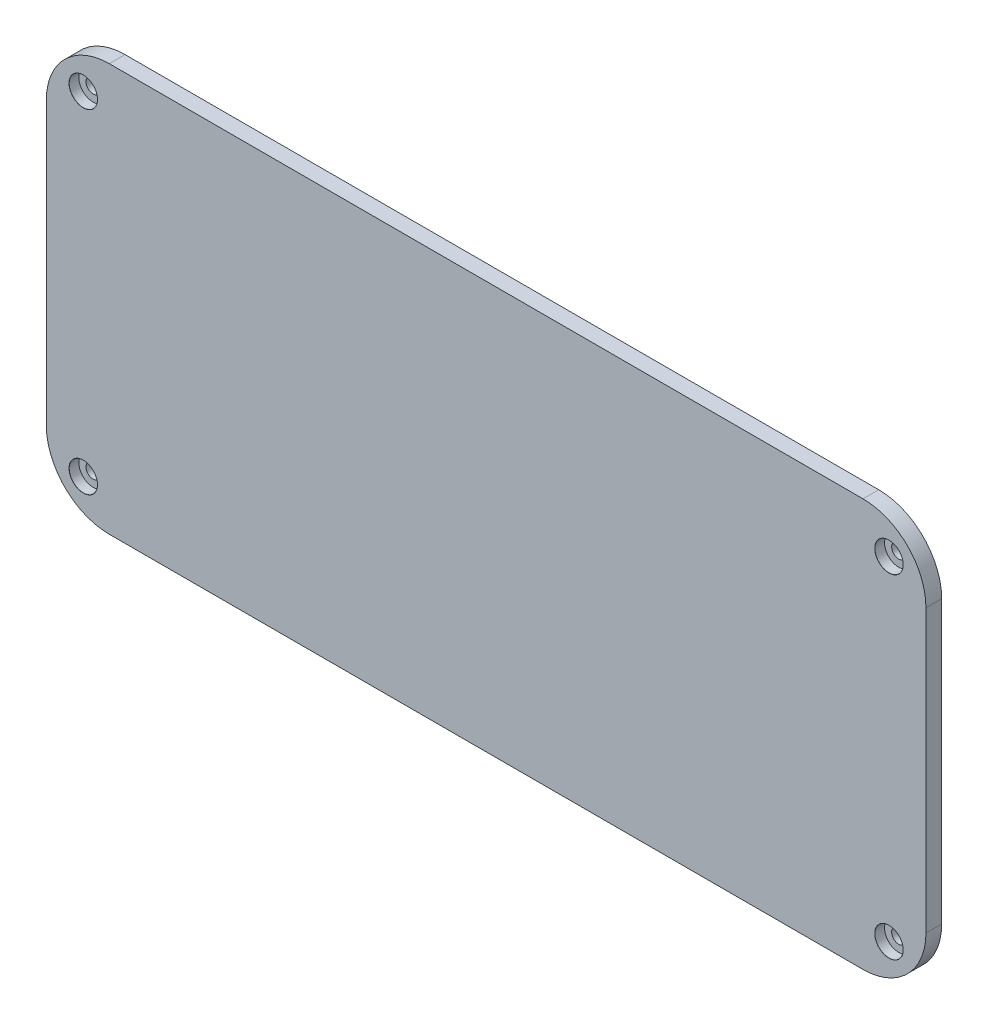
SolidWorks part; units mm, degrees
ref_plane "Front Plane" through (0, 0, 0) normal (0, 0, 1) x (1, 0, 0)
ref_plane "Top Plane" through (0, 0, 0) normal (0, 1, 0) x (1, 0, 0)
ref_plane "Right Plane" through (0, 0, 0) normal (1, 0, 0) x (0, 0, -1)
sketch "Sketch1" plane through (0, 0, 0) normal (0, 0, 1) x (1, 0, 0)
  line L0 (-119.75, 64.75) -> (119.75, 64.75)
  line L5 (-139.75, 44.75) -> (-139.75, -44.75)
  line L6 (-119.75, -64.75) -> (119.75, -64.75)
  line L7 (139.75, 44.75) -> (139.75, -44.75)
  arc A0 (-119.75, -64.75) -> (-139.75, -44.75) centre (-119.75, -44.75) cw
  arc A1 (-139.75, 44.75) -> (-119.75, 64.75) centre (-119.75, 44.75) cw
  arc A2 (119.75, 64.75) -> (139.75, 44.75) centre (119.75, 44.75) cw
  arc A3 (139.75, -44.75) -> (119.75, -64.75) centre (119.75, -44.75) cw
  point P7 (0, 64.75)
  point P8 (0, -64.75)
  point P9 (-139.75, 0)
  point P16 (0, 0)
  point P17 (0, 0)
  dimension "D3" = 20
  dimension "D4" = 20
  dimension "D1" = 239.5
  dimension "D2" = 89.5
extrude "Boss-Extrude1" add sketch "Sketch1" along normal blind 5
hole_wizard "CBORE for M4 Pan Head Machine Screw1" positions "Sketch2" profile "Sketch3" counterbore size "M4" standard "ANSI Metric"
sketch "Sketch2" plane through (0, 0, 5) normal (0, 0, 1) x (1, 0, 0)
  point P0 (-128, 53)
  point P2 (-128, -53)
  point P4 (128, 53)
  point P6 (128, -53)
  point P21 (0, 0)
  dimension "D1" = 128
  dimension "D2" = 53
  dimension "D3" = 53
  dimension "D4" = 128
sketch "Sketch3" plane through (-128, 53, 5) normal (1, 0, 0) x (0, -1, 0)
  line L0 (0, 0) -> (0, 31.3519)
  line L1 (0, 31.3519) -> (2.25, 30)
  line L2 (2.25, 30) -> (2.25, 3.1)
  line L3 (2.25, 3.1) -> (4.5, 3.1)
  line L5 (4.5, 3.1) -> (4.5, 0.025)
  line L6 (4.5, 0.025) -> (4.525, 0)
  line L7 (4.525, 0) -> (0, 0)
  line L8 (-4.5, 0.025) -> (-4.525, 0) construction
  line L10 (0, 31.3519) -> (-2.25, 30) construction
  line L11 (0, -6.35) -> (0, 107.95) construction
  dimension "Hole Dia." = 4.5
  dimension "Hole Depth" = 30
  dimension "C'Bore Dia." = 9
  dimension "C'Bore Depth" = 3.1
  dimension "Near C'Sink Dia." = 9.05
  dimension "Near C'Sink Angle" = 90
  dimension "Drill Angle" = 118
sketch "Sketch4" plane through (0, 0, 0) normal (0, 0, -1) x (-1, 0, 0)
  line L1 (-37.75, 27.75) -> (37.75, 27.75)
  line L2 (-37.75, 27.75) -> (-37.75, -27.75)
  line L3 (-37.75, -27.75) -> (37.75, -27.75)
  line L4 (37.75, 27.75) -> (37.75, -27.75)
  line L5 (-37.75, 27.75) -> (37.75, -27.75) construction
  line L6 (-37.75, -27.75) -> (37.75, 27.75) construction
  line L7 (-47.75, 37.75) -> (47.75, 37.75)
  line L8 (-47.75, 37.75) -> (-47.75, -37.75)
  line L9 (-47.75, -37.75) -> (47.75, -37.75)
  line L10 (47.75, 37.75) -> (47.75, -37.75)
  line L11 (-47.75, 37.75) -> (47.75, -37.75) construction
  line L12 (-47.75, -37.75) -> (47.75, 37.75) construction
  point P0 (0, 0)
  point P6 (0, 0)
  dimension "D1" = 75.5
  dimension "D2" = 55.5
  dimension "D3" = 10
  dimension "D4" = 10
extrude "Boss-Extrude2" add sketch "Sketch4" along normal blind 10
